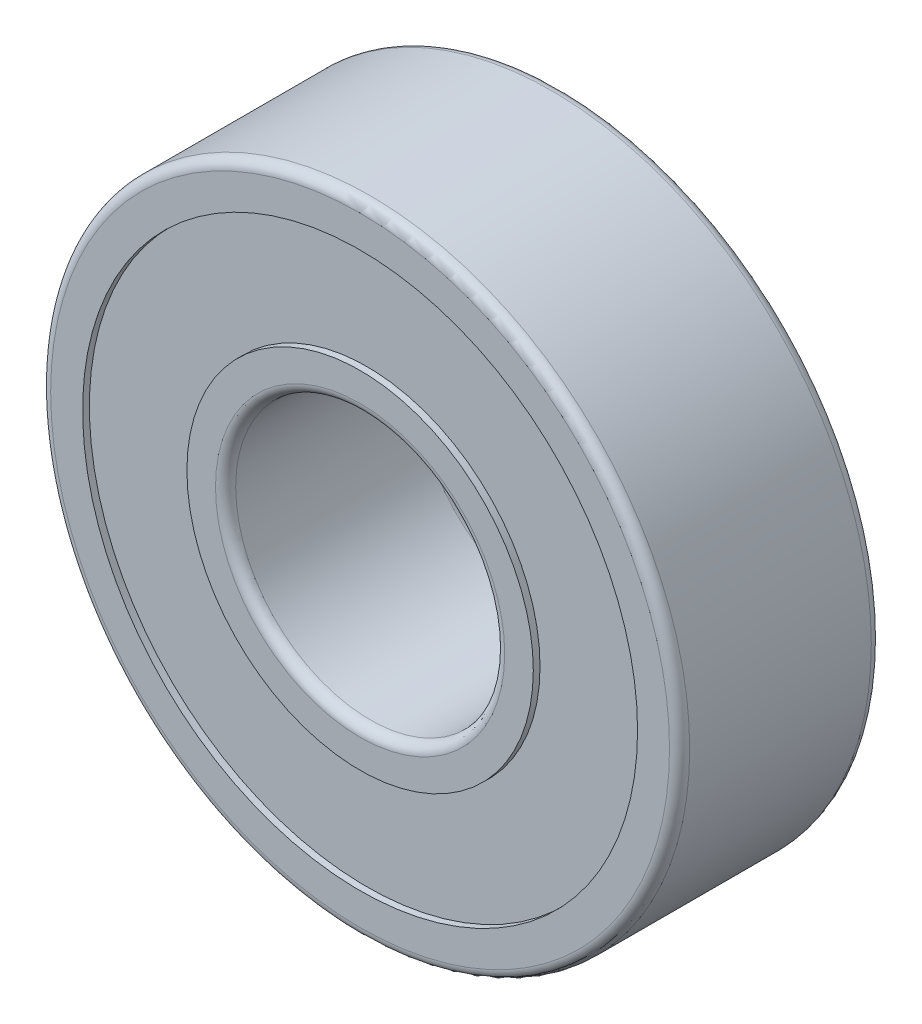
SolidWorks part; units mm, degrees
material "AISI 1045 Steel, cold drawn"
ref_plane "前视基准面" through (0, 0, 0) normal (0, 0, 1) x (1, 0, 0)
ref_plane "上视基准面" through (0, 0, 0) normal (0, 1, 0) x (1, 0, 0)
ref_plane "右视基准面" through (0, 0, 0) normal (1, 0, 0) x (0, 0, -1)
sketch "草图1" plane through (0, 0, 0) normal (0, 0, 1) x (1, 0, 0)
  circle A0 centre (0, 0) radius 4
  circle A1 centre (0, 0) radius 9.5
  dimension "D1" = 8
  dimension "D2" = 19
extrude "拉伸1" add sketch "草图1" along normal mid plane 6
sketch "草图2" plane through (0, 0, 3) normal (0, 0, 1) x (1, 0, 0)
  circle A0 centre (0, 0) radius 5.15
  circle A1 centre (0, 0) radius 8.25
  dimension "D1" = 10.3
  dimension "D2" = 16.5
extrude "拉伸2" cut sketch "草图2" against normal blind 0.2
mirror "镜向1" about plane through (0, 0, 0) normal (0, 0, 1) of "拉伸2"
fillet "圆角1" radius 0.3 4 edges at (4, 0, -3) (4, 0, 3) (9.5, 0, -3) (9.5, 0, 3)
